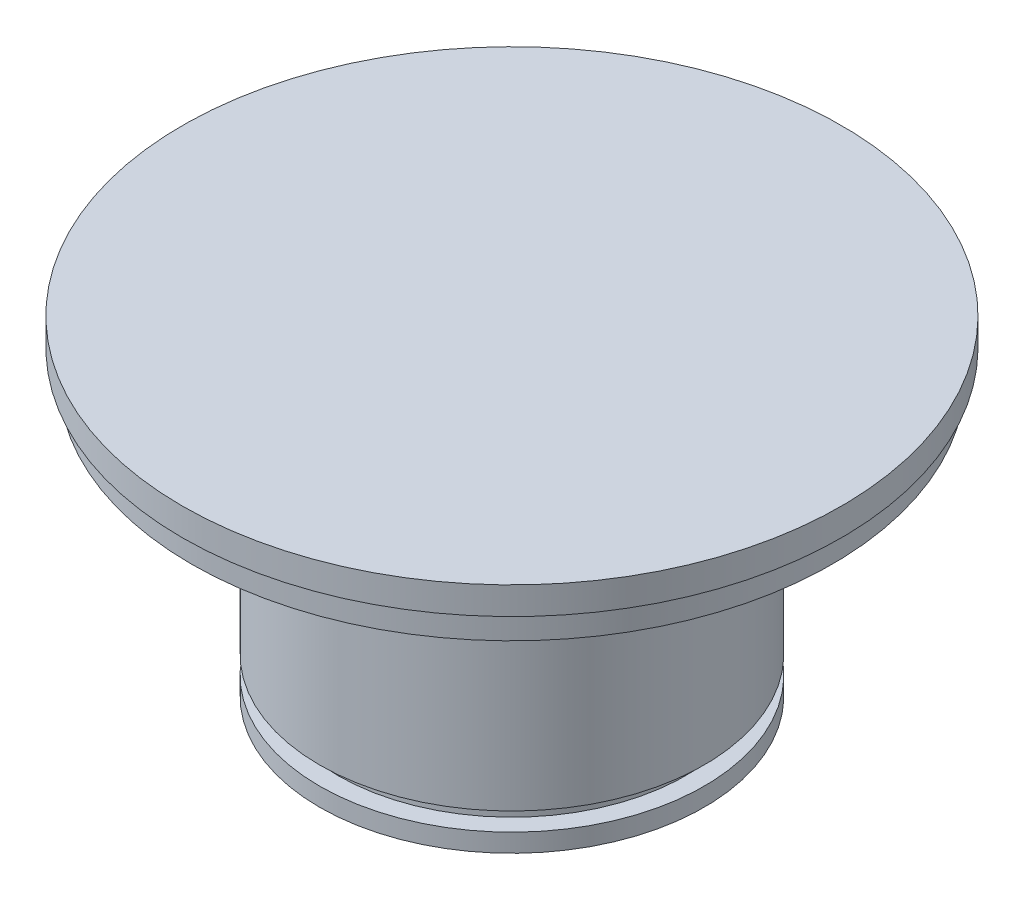
SolidWorks part; units mm, degrees
ref_plane "Front Plane" through (0, 0, 0) normal (0, 0, 1) x (1, 0, 0)
ref_plane "Top Plane" through (0, 0, 0) normal (0, 1, 0) x (1, 0, 0)
ref_plane "Right Plane" through (0, 0, 0) normal (1, 0, 0) x (0, 0, -1)
sketch "Sketch1" plane through (0, 0, 0) normal (0, 1, 0) x (1, 0, 0)
  circle A0 centre (0, 0) radius 18
  dimension "D1" = 36
extrude "Boss-Extrude1" add sketch "Sketch1" along normal blind 1.5
sketch "Sketch2" plane through (0, 0, 0) normal (0, -1, 0) x (1, 0, 0)
  circle A0 centre (0, 0) radius 17.5
  dimension "D1" = 35
extrude "Boss-Extrude2" add sketch "Sketch2" along normal blind 1.5
sketch "Sketch3" plane through (0, -1.5, 0) normal (0, -1, 0) x (1, 0, 0)
  circle A0 centre (0, 0) radius 12
  dimension "D1" = 24
extrude "Boss-Extrude3" add sketch "Sketch3" along normal blind 1
sketch "Sketch4" plane through (0, -2.5, 0) normal (0, -1, 0) x (1, 0, 0)
  circle A0 centre (0, 0) radius 10.5
  dimension "D1" = 21
extrude "Boss-Extrude4" add sketch "Sketch4" along normal blind 12
sketch "Sketch5" plane through (0, -14.5, 0) normal (0, -1, 0) x (1, 0, 0)
  circle A0 centre (0, 0) radius 9.5
  dimension "D1" = 19
extrude "Boss-Extrude5" add sketch "Sketch5" along normal blind 1
sketch "Sketch6" plane through (0, -15.5, 0) normal (0, -1, 0) x (1, 0, 0)
  circle A0 centre (0, 0) radius 10.5 construction
  circle A1 centre (0, 0) radius 10.5
extrude "Boss-Extrude6" add sketch "Sketch6" along normal blind 1
sketch "Sketch7" plane through (0, 0, 0) normal (0, 0, 1) x (1, 0, 0)
  line L0 (0, -16.5) -> (0, 1.5) construction
  line L1 (-10.5, -16.5) -> (10.5, -16.5) construction
  line L2 (18, 1.5) -> (-18, 1.5) construction
  line L3 (-8.5, -16.5) -> (0, -16.5)
  line L4 (0, -16.5) -> (0, -8)
  arc A0 (0, -8) -> (-8.5, -16.5) centre (0, -16.5) ccw
  dimension "D1" = 17
